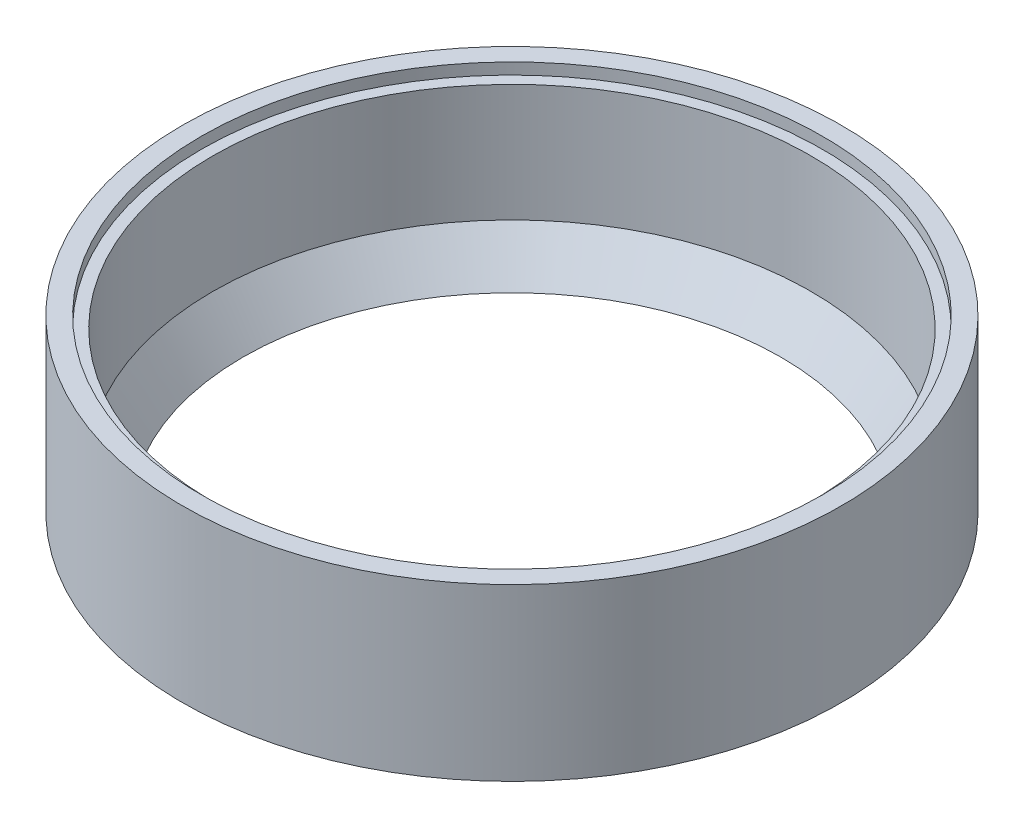
SolidWorks part; units mm, degrees
ref_plane "Plan de face" through (0, 0, 0) normal (0, 0, 1) x (1, 0, 0)
ref_plane "Plan de dessus" through (0, 0, 0) normal (0, 1, 0) x (1, 0, 0)
ref_plane "Plan de droite" through (0, 0, 0) normal (1, 0, 0) x (0, 0, -1)
sketch "Esquisse1" plane through (0, 0, 0) normal (0, 0, 1) x (1, 0, 0)
  line L0 (0, 40.5469) -> (0, -22.4609) construction
  line L1 (71, 2.8123) -> (75, 2.8123)
  line L2 (75, 2.8123) -> (75, 7.8123)
  line L3 (75, 7.8123) -> (80, 7.8123)
  line L4 (80, 7.8123) -> (80, 2.8123)
  line L5 (80, 2.8123) -> (87, 2.8123)
  line L6 (79, 44.8123) -> (79, 13.8123)
  line L7 (87, 2.8123) -> (87, 47.8123)
  line L8 (87, 47.8123) -> (82, 47.8123)
  line L9 (82, 47.8123) -> (82, 44.8123)
  line L10 (82, 44.8123) -> (79, 44.8123)
  line L11 (79, 13.8123) -> (71, 2.8123)
  point P5 (84.5, 47.8123)
  point P13 (75, 5.3123)
  dimension "D1" = 45
  dimension "D2" = 3
  dimension "D3" = 4
  dimension "D4" = 5
  dimension "D5" = 7
  dimension "D6" = 3
  dimension "D7" = 5
  dimension "D8" = 31
  dimension "D9" = 5
  dimension "D10" = 71
revolve "Révolution1" add sketch "Esquisse1" angle 360 about L0
